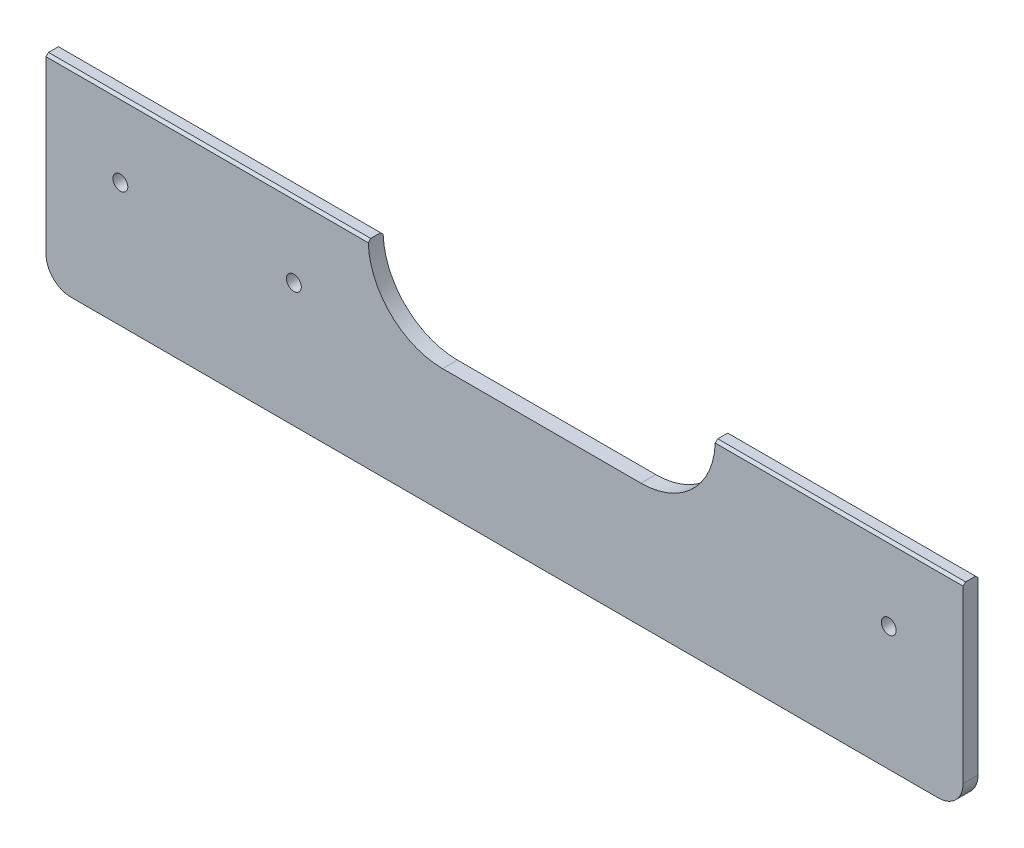
SolidWorks part; units mm, degrees
ref_plane "前视基准面" through (0, 0, 0) normal (0, 0, 1) x (1, 0, 0)
ref_plane "上视基准面" through (0, 0, 0) normal (0, 1, 0) x (1, 0, 0)
ref_plane "右视基准面" through (0, 0, 0) normal (1, 0, 0) x (0, 0, -1)
other "Configuration Table"
sketch "草图1" plane through (0, 0, 0) normal (0, 0, 1) x (1, 0, 0)
  line L1 (-110, 15) -> (75, 15)
  line L2 (-110, 15) -> (-110, -25)
  line L3 (-110, -25) -> (75, -25)
  line L4 (75, 15) -> (75, -25)
  dimension "D1" = 185
  dimension "D2" = 40
  dimension "D3" = 15
  dimension "D4" = 110
extrude "凸台-拉伸1" add sketch "草图1" along normal blind 3
sketch "草图2" plane through (0, 0, 3) normal (0, 0, 1) x (1, 0, 0)
  circle A0 centre (60, 0) radius 1.5
  circle A1 centre (-60, 0) radius 1.5
  point P4 (0, 0)
  dimension "D1" = 3
  dimension "D2" = 3
  dimension "D3" = 120
  dimension "D4" = 60
extrude "切除-拉伸1" cut sketch "草图2" against normal blind 3
sketch "草图3" plane through (0, 0, 3) normal (0, 0, 1) x (1, 0, 0)
  line L0 (-30, 15) -> (10, 15) construction
  line L1 (-30, 30) -> (10, 30)
  line L2 (-30, 0) -> (10, 0)
  arc A0 (-30, 30) -> (-30, 0) centre (-30, 15) ccw
  arc A1 (10, 0) -> (10, 30) centre (10, 15) ccw
  point P2 (-10, 15)
  dimension "D1" = 15
  dimension "D2" = 15
  dimension "D3" = 40
  dimension "D4" = 30
extrude "切除-拉伸2" cut sketch "草图3" against normal blind 3
fillet "圆角1" radius 5 2 edges at (-110, -25, 1.5) (75, -25, 1.5)
sketch "草图4" plane through (0, 0, 3) normal (0, 0, 1) x (1, 0, 0)
  circle A0 centre (-95, 0) radius 1.5
  circle A1 centre (-60, 0) radius 1.5 construction
  point P4 (0, 0)
  dimension "D1" = 35
  dimension "D2" = 3
extrude "切除-拉伸3" cut sketch "草图4" against normal blind 3
chamfer "倒角1" distance 0.5 angle 45 4 edges at (50, 15, 0) (-77.5, 15, 0) (50, 15, 3) (-77.5, 15, 3)
